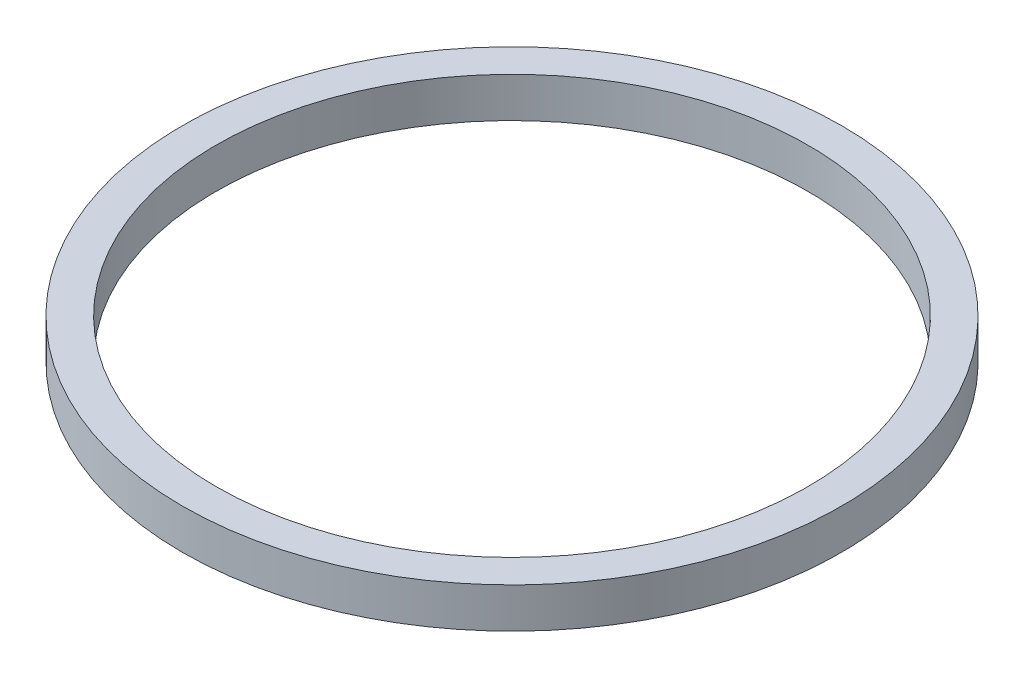
SolidWorks part; units mm, degrees
ref_plane "Front Plane" through (0, 0, 0) normal (0, 0, 1) x (1, 0, 0)
ref_plane "Top Plane" through (0, 0, 0) normal (0, 1, 0) x (1, 0, 0)
ref_plane "Right Plane" through (0, 0, 0) normal (1, 0, 0) x (0, 0, -1)
sketch "Sketch3" plane through (0, -876.833, 0) normal (0, 1, 0) x (1, 0, 0)
  circle A0 centre (1340.7701, 694.1179) radius 11.0719
  circle A1 centre (1340.7701, 694.1179) radius 12.3323
extrude "Boss-Extrude2" add sketch "Sketch3" along normal blind 1.5
